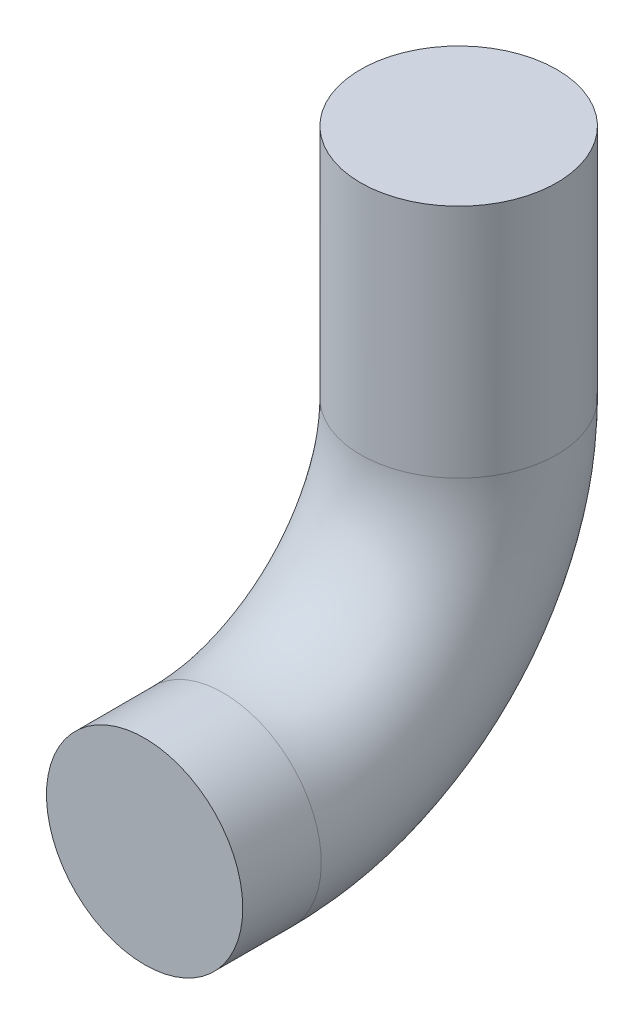
SolidWorks part; units mm, degrees
ref_plane "Plan de face" through (0, 0, 0) normal (0, 0, 1) x (1, 0, 0)
ref_plane "Plan de dessus" through (0, 0, 0) normal (0, 1, 0) x (1, 0, 0)
ref_plane "Plan de droite" through (0, 0, 0) normal (1, 0, 0) x (0, 0, -1)
sketch "Esquisse5" plane through (0, 0, 0) normal (0, 0, 1) x (1, 0, 0)
  line L0 (0, 0) -> (0, -3) construction
  line L1 (-1.0708, 0) -> (1.5915, 0) construction
  circle A0 centre (0, -3) radius 1.25
  dimension "D1" = 2.5
  dimension "D2" = 3
revolve "Révolution1" add sketch "Esquisse5" angle 90 about L1
sketch "Esquisse6" plane through (0, 0, 0) normal (0, 0, 1) x (1, 0, 0)
  circle A1 centre (0, -3) radius 1.25
  circle A2 centre (0, -3) radius 1.25
  dimension "D1" = 0
extrude "Boss.-Extru.3" add sketch "Esquisse6" along normal blind 1
sketch "Esquisse7" plane through (0, 0, 0) normal (0, 1, 0) x (1, 0, 0)
  circle A1 centre (0, 3) radius 1.25
  circle A2 centre (0, 3) radius 1.25
  dimension "D1" = 0
extrude "Boss.-Extru.4" add sketch "Esquisse7" along normal blind 3 contours A2
